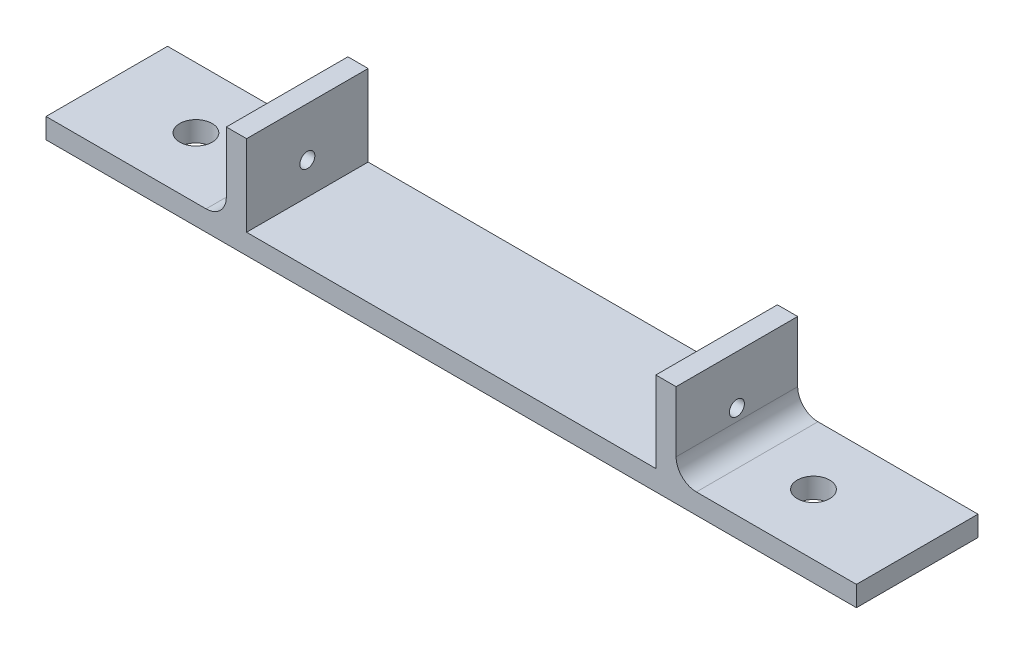
SolidWorks part; units mm, degrees
ref_plane "Front Plane" through (0, 0, 0) normal (0, 0, 1) x (1, 0, 0)
ref_plane "Top Plane" through (0, 0, 0) normal (0, 1, 0) x (1, 0, 0)
ref_plane "Right Plane" through (0, 0, 0) normal (1, 0, 0) x (0, 0, -1)
sketch "Sketch1" plane through (0, 0, 0) normal (0, 1, 0) x (1, 0, 0)
  line L1 (100, -15) -> (-100, -15)
  line L2 (100, -15) -> (100, 15)
  line L3 (100, 15) -> (-100, 15)
  line L4 (-100, -15) -> (-100, 15)
  line L5 (100, -15) -> (-100, 15) construction
  line L6 (100, 15) -> (-100, -15) construction
  point P0 (0, 0)
  dimension "D1" = 200
  dimension "D2" = 30
extrude "Boss-Extrude1" add sketch "Sketch1" along normal blind 5
sketch "Sketch2" plane through (0, 5, 0) normal (0, 1, 0) x (1, 0, 0)
  line L0 (0, 15) -> (0, -16.5335) construction
  line L1 (100, 15) -> (-100, 15) construction
  line L2 (-100, 0) -> (100, 0) construction
  line L3 (-100, 15) -> (-100, -15) construction
  line L4 (100, -15) -> (100, 15) construction
  line L6 (-50.5, -15) -> (-55.5, -15)
  line L7 (-50.5, -15) -> (-50.5, 15)
  line L8 (-50.5, 15) -> (-55.5, 15)
  line L9 (-55.5, -15) -> (-55.5, 15)
  line L10 (-50.5, -15) -> (-55.5, 15) construction
  line L11 (-50.5, 15) -> (-55.5, -15) construction
  line L12 (55.5, -15) -> (50.5, -15)
  line L13 (55.5, -15) -> (55.5, 15)
  line L14 (55.5, 15) -> (50.5, 15)
  line L15 (50.5, -15) -> (50.5, 15)
  line L16 (55.5, -15) -> (50.5, 15) construction
  line L17 (55.5, 15) -> (50.5, -15) construction
  point P11 (-53, 0)
  point P16 (53, 0)
  point P23 (-4.7082, 0)
  dimension "D1" = 5
  dimension "D2" = 5
  dimension "D3" = 106
  dimension "D4" = 53
extrude "Boss-Extrude2" add sketch "Sketch2" along normal blind 20
fillet "Fillet1" radius 5 2 edges at (55.5, 5, 0) (-55.5, 5, 0)
sketch "Sketch3" plane through (-55.5, 0, 0) normal (-1, 0, 0) x (0, 0, 1)
  line L0 (0, 25) -> (0, 5) construction
  line L1 (-15, 25) -> (15, 25) construction
  line L2 (-15, 5) -> (15, 5) construction
  circle A1 centre (0, 12.94) radius 1.85
  dimension "D2" = 3.7
  dimension "D3" = 7.94
extrude "Cut-Extrude2" cut sketch "Sketch3" against normal through all
sketch "Sketch4" plane through (0, 5, 0) normal (0, 1, 0) x (1, 0, 0)
  line L0 (-100, 0) -> (-50.5, 0) construction
  line L1 (-100, 15) -> (-100, -15) construction
  line L2 (-50.5, -15) -> (-50.5, 15) construction
  circle A0 centre (-78, 0) radius 4
  dimension "D2" = 8
  dimension "D1" = 22
extrude "Cut-Extrude3" cut sketch "Sketch4" against normal through all
sketch "Sketch5" plane through (0, 5, 0) normal (0, 1, 0) x (1, 0, 0)
  circle A0 centre (74.4, 0) radius 4
  dimension "D1" = 8
extrude "Cut-Extrude4" cut sketch "Sketch5" against normal through all
